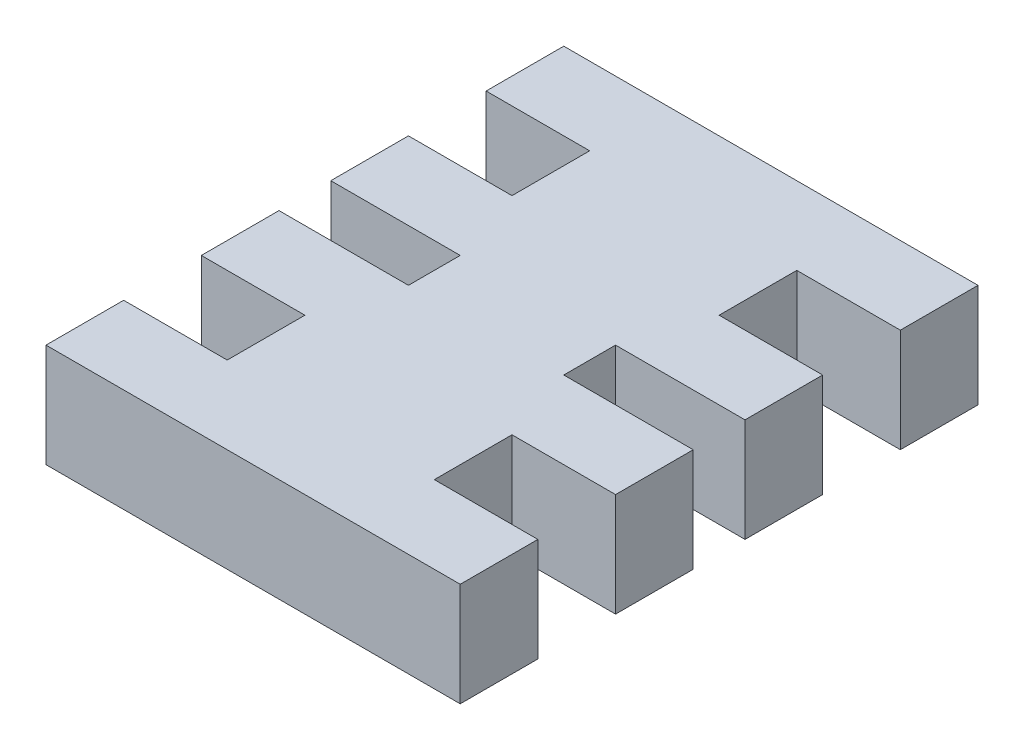
SolidWorks part; units mm, degrees
material "Brass"
ref_plane "Front Plane" through (0, 0, 0) normal (0, 0, 1) x (1, 0, 0)
ref_plane "Top Plane" through (0, 0, 0) normal (0, 1, 0) x (1, 0, 0)
ref_plane "Right Plane" through (0, 0, 0) normal (1, 0, 0) x (0, 0, -1)
sketch "Sketch1" plane through (0, 0, 0) normal (0, 1, 0) x (1, 0, 0)
  line L0 (-130.4032, 0) -> (149.2742, 0) construction
  line L1 (0, 80.6855) -> (0, -80.2016) construction
  line L2 (40, 55) -> (-40, 55)
  line L3 (-40, 40) -> (-20, 40)
  line L4 (-20, 40) -> (-20, 25)
  line L5 (-20, 25) -> (-40, 25)
  line L6 (-40, 25) -> (-40, 10)
  line L7 (-40, 10) -> (-15, 10)
  line L8 (-15, 10) -> (-15, 0)
  line L9 (-15, 0) -> (-40, 0)
  line L10 (-40, 0) -> (-40, -15)
  line L11 (-40, -15) -> (-20, -15)
  line L12 (-20, -15) -> (-20, -30)
  line L13 (-20, -30) -> (-40, -30)
  line L14 (-40, -30) -> (-40, -45)
  line L15 (-40, -45) -> (40, -45)
  line L16 (-40, 55) -> (-40, 40)
  line L17 (40, -30) -> (40, -45)
  line L18 (20, -30) -> (40, -30)
  line L19 (20, -15) -> (20, -30)
  line L20 (40, -15) -> (20, -15)
  line L21 (40, 0) -> (40, -15)
  line L22 (15, 0) -> (40, 0)
  line L23 (15, 10) -> (15, 0)
  line L24 (40, 10) -> (15, 10)
  line L25 (40, 25) -> (40, 10)
  line L26 (20, 25) -> (40, 25)
  line L27 (20, 40) -> (20, 25)
  line L28 (40, 40) -> (20, 40)
  line L29 (40, 55) -> (40, 40)
  point P24 (0, -45)
  point P37 (0, 55)
  dimension "D1" = 15
  dimension "D2" = 10
  dimension "D3" = 15
  dimension "D4" = 15
  dimension "D5" = 20
  dimension "D6" = 25
  dimension "D7" = 40
  dimension "D8" = 40
  dimension "D9" = 40
  dimension "D10" = 40
  dimension "D11" = 15
  dimension "D12" = 15
  dimension "D13" = 15
  dimension "D14" = 20
extrude "Boss-Extrude1" add sketch "Sketch1" along normal blind 20
